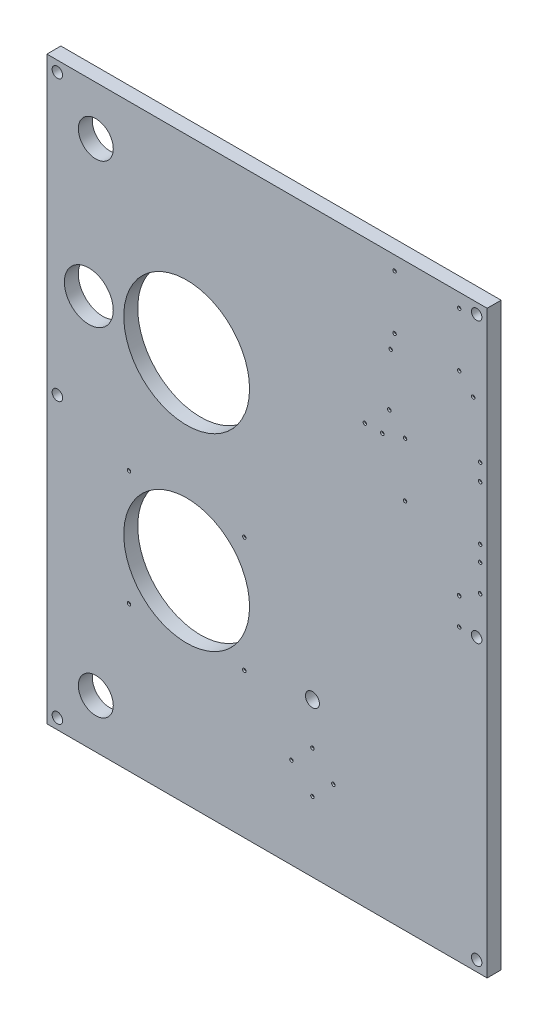
SolidWorks part; units mm, degrees
material "PVC Rigid"
ref_plane "Front Plane" through (0, 0, 0) normal (0, 0, 1) x (1, 0, 0)
ref_plane "Top Plane" through (0, 0, 0) normal (0, 1, 0) x (1, 0, 0)
ref_plane "Right Plane" through (0, 0, 0) normal (1, 0, 0) x (0, 0, -1)
sketch "Sketch2" plane through (0, 0, 0) normal (0, 0, 1) x (1, 0, 0)
  line L0 (-190.5, 254) -> (190.5, 254)
  line L1 (-200.025, -263.525) -> (200.025, -263.525)
  line L2 (-200.025, -263.525) -> (-200.025, 263.525)
  line L3 (-200.025, 263.525) -> (200.025, 263.525)
  line L4 (200.025, -263.525) -> (200.025, 263.525)
  line L5 (-200.025, -263.525) -> (200.025, 263.525) construction
  line L6 (-200.025, 263.525) -> (200.025, -263.525) construction
  line L7 (190.5, -254) -> (190.5, 254)
  line L8 (-190.5, -254) -> (190.5, -254)
  line L9 (-190.5, -254) -> (-190.5, 254)
  circle A0 centre (-190.5, 254) radius 4.7625
  circle A1 centre (190.5, 254) radius 4.7625
  circle A2 centre (-190.5, -254) radius 4.7625
  circle A3 centre (190.5, -254) radius 4.7625
  circle A4 centre (-190.5, 0) radius 4.7625
  circle A5 centre (190.5, 0) radius 4.7625
  point P0 (0, 0)
  dimension "D4" = 9.525
  dimension "D5" = 9.525
  dimension "D6" = 9.525
  dimension "D7" = 9.525
  dimension "D8" = 9.525
  dimension "D9" = 9.525
  dimension "D1" = 508
  dimension "D2" = 381
  dimension "D3" = 9.525
extrude "Boss-Extrude1" add sketch "Sketch2" along normal blind 12.7 contours A5 L7 A1 L0 A0 L9 A4 A2 L8 A3 | L1 L4 L3 L2 A5 L7 A3 L8 A2 L9 A4 A0 L0 A1
sketch "Sketch3" plane through (0, 0, 12.7) normal (0, 0, 1) x (1, 0, 0)
  line L0 (-200.025, 263.525) -> (200.025, 263.525) construction
  line L1 (-200.025, -263.525) -> (-200.025, 263.525) construction
  line L2 (-200.025, -263.525) -> (200.025, -263.525) construction
  line L3 (-182.5625, 198.4375) -> (-20.6375, 198.4375) construction
  line L4 (-20.6375, 198.4375) -> (-20.6375, 36.5125) construction
  line L5 (-20.6375, 36.5125) -> (-182.5625, 36.5125) construction
  line L6 (-182.5625, 36.5125) -> (-182.5625, 198.4375) construction
  circle A0 centre (-155.575, 219.075) radius 15.875
  circle A1 centre (-161.925, 92.075) radius 22.225
  circle A2 centre (-73.025, 92.075) radius 57.15
  circle A3 centre (-73.025, -79.375) radius 57.15
  circle A4 centre (-155.575, -219.075) radius 15.875
  circle A5 centre (-182.5625, 198.4375) radius 1.5875 construction
  circle A6 centre (-20.6375, 198.4375) radius 1.5875 construction
  circle A7 centre (-20.6375, 36.5125) radius 1.5875 construction
  circle A8 centre (-182.5625, 36.5125) radius 1.5875 construction
  dimension "D1" = 31.75
  dimension "D4" = 44.45
  dimension "D9" = 114.3
  dimension "D10" = 114.3
  dimension "D12" = 171.45
  dimension "D13" = 31.75
  dimension "D16" = 3.175
  dimension "D2" = 44.45
  dimension "D3" = 44.45
  dimension "D5" = 38.1
  dimension "D6" = 171.45
  dimension "D7" = 127
  dimension "D8" = 171.45
  dimension "D11" = 127
  dimension "D14" = 44.45
  dimension "D15" = 44.45
  dimension "D17" = 17.4625
  dimension "D18" = 161.925
  dimension "D19" = 161.925
  dimension "D20" = 65.0875
extrude "Cut-Extrude1" cut sketch "Sketch3" against normal through all
sketch "Sketch4" plane through (0, 0, 12.7) normal (0, 0, 1) x (1, 0, 0)
  line L0 (-200.025, -263.525) -> (-200.025, 263.525) construction
  line L1 (200.025, -263.525) -> (200.025, 263.525) construction
  line L2 (-200.025, 263.525) -> (200.025, 263.525) construction
  line L3 (193.675, 263.525) -> (193.675, -263.525) construction
  line L4 (-200.025, -263.525) -> (200.025, -263.525) construction
  line L5 (193.675, 123.825) -> (125.4125, 123.825) construction
  line L6 (125.4125, 123.825) -> (125.4125, 74.6125) construction
  line L7 (125.4125, 74.6125) -> (193.675, 74.6125) construction
  line L8 (125.4125, 117.475) -> (102.3686, 117.475) construction
  line L9 (112.395, 187.325) -> (187.325, 187.325) construction
  line L10 (115.8875, 250.825) -> (174.625, 250.825) construction
  line L11 (115.8875, 250.825) -> (115.8875, 201.6125) construction
  line L12 (115.8875, 201.6125) -> (174.625, 201.6125) construction
  line L13 (174.625, 250.825) -> (174.625, 201.6125) construction
  line L14 (127.526, 139.065) -> (205.4515, 139.065) construction
  line L15 (41.275, -161.925) -> (41.275, -200.025) construction
  circle A0 centre (60.325, -180.975) radius 1.5875
  circle A1 centre (22.225, -180.975) radius 1.5875
  circle A2 centre (41.275, -161.925) radius 1.5875
  circle A3 centre (193.675, 35.7188) radius 1.5875
  circle A4 centre (174.625, 0) radius 1.5875
  circle A5 centre (-73.025, -79.375) radius 57.15 construction
  circle A6 centre (193.675, 60.325) radius 1.5875
  circle A8 centre (193.675, 74.6125) radius 1.5875
  circle A9 centre (193.675, 123.825) radius 1.5875
  circle A10 centre (125.4125, 123.825) radius 1.5875
  circle A11 centre (125.4125, 74.6125) radius 1.5875
  circle A12 centre (88.9, 117.475) radius 1.5875
  circle A13 centre (104.775, 117.475) radius 1.5875
  circle A14 centre (115.8875, 250.825) radius 1.5875
  circle A15 centre (174.625, 250.825) radius 1.5875
  circle A16 centre (174.625, 201.6125) radius 1.5875
  circle A17 centre (115.8875, 201.6125) radius 1.5875
  circle A18 centre (112.395, 187.325) radius 1.5875
  circle A19 centre (187.325, 187.325) radius 1.5875
  circle A20 centre (111.125, 139.065) radius 1.5875
  circle A21 centre (193.675, 139.065) radius 1.5875
  circle A22 centre (41.275, -200.025) radius 1.5875
  circle A23 centre (174.625, 24.6063) radius 1.5875
  line B0 (-125.4125, -26.9875) -> (-20.6375, -26.9875) construction
  line B1 (-125.4125, -26.9875) -> (-125.4125, -131.7625) construction
  line B2 (-125.4125, -131.7625) -> (-20.6375, -131.7625) construction
  line B3 (-20.6375, -26.9875) -> (-20.6375, -131.7625) construction
  circle B4 centre (-125.4125, -26.9875) radius 1.5875
  circle B5 centre (-20.6375, -26.9875) radius 1.5875
  circle B6 centre (-20.6375, -131.7625) radius 1.5875
  circle B7 centre (-125.4125, -131.7625) radius 1.5875
  dimension "D5" = 3.175
  dimension "D6" = 52.3875
  dimension "D4" = 3.175
  dimension "D9" = 3.175
  dimension "D10" = 124.46
  dimension "D15" = 3.175
  dimension "D32" = 3.175
  dimension "D33" = 3.175
  dimension "D8" = 3.175
  dimension "D11" = 3.175
  dimension "D13" = 1.27
  dimension "D7" = 52.3875
  dimension "D12" = 6.35
  dimension "D14" = 203.2
  dimension "D17" = 139.7
  dimension "D18" = 68.2625
  dimension "D19" = 49.2125
  dimension "D20" = 6.35
  dimension "D21" = 15.875
  dimension "D22" = 95.25
  dimension "D23" = 58.7375
  dimension "D24" = 25.4
  dimension "D25" = 12.7
  dimension "D26" = 49.2125
  dimension "D27" = 74.93
  dimension "D28" = 76.2
  dimension "D29" = 12.7
  dimension "D34" = 158.75
  dimension "D35" = 38.1
  dimension "D36" = 63.5
sketch_block_instance "Block1-1"
sketch_block "Block1" parameters "D1"=3.175
extrude "Cut-Extrude2" cut sketch "Sketch4" against normal blind 1.5875
sketch "Sketch7" plane through (0, 0, 12.7) normal (0, 0, 1) x (1, 0, 0)
  line L0 (41.275, -123.825) -> (41.275, -163.5125) construction
  line L1 (200.025, -263.525) -> (200.025, 263.525) construction
  circle A0 centre (41.275, -123.825) radius 6.35
  circle A1 centre (41.275, -161.925) radius 1.5875 construction
  dimension "D2" = 12.7
  dimension "D1" = 39.6875
extrude "Cut-Extrude4" cut sketch "Sketch7" against normal through all
sketch "Sketch8" [suppressed] plane through (0, 0, 12.7) normal (0, 0, 1) x (1, 0, 0)
  line L0 (122.2375, 250.825) -> (168.275, 250.825) construction
  line L1 (122.2375, 253.365) -> (168.275, 253.365)
  line L2 (122.2375, 248.285) -> (168.275, 248.285)
  line L3 (168.275, 250.825) -> (174.625, 250.825) construction
  line L4 (122.2375, 201.6125) -> (168.275, 201.6125) construction
  line L5 (122.2375, 204.1525) -> (168.275, 204.1525)
  line L6 (122.2375, 199.0725) -> (168.275, 199.0725)
  line L7 (115.8875, 201.6125) -> (122.2375, 201.6125) construction
  line L8 (174.625, 244.475) -> (174.625, 207.9625) construction
  line L9 (177.165, 244.475) -> (177.165, 207.9625)
  line L10 (172.085, 244.475) -> (172.085, 207.9625)
  line L11 (145.2562, 250.825) -> (145.2562, 201.6125) construction
  line L12 (115.8875, 244.475) -> (115.8875, 207.9625) construction
  line L13 (113.3475, 244.475) -> (113.3475, 207.9625)
  line L14 (118.4275, 244.475) -> (118.4275, 207.9625)
  line L15 (118.745, 187.325) -> (180.975, 187.325) construction
  line L16 (118.745, 189.865) -> (180.975, 189.865)
  line L17 (118.745, 184.785) -> (180.975, 184.785)
  line L18 (118.745, 187.325) -> (112.395, 187.325) construction
  line L19 (112.395, 187.325) -> (112.395, 139.2316) construction
  line L20 (112.395, 139.2316) -> (193.3575, 139.2316) construction
  line L21 (149.86, 187.325) -> (149.86, 139.2316) construction
  line L22 (112.395, 163.2783) -> (183.6375, 163.2783) construction
  line L23 (118.745, 139.2316) -> (187.0075, 139.2316) construction
  line L24 (118.745, 141.7716) -> (187.0075, 141.7716)
  line L25 (118.745, 136.6916) -> (187.0075, 136.6916)
  line L26 (112.395, 180.975) -> (112.395, 145.5816) construction
  line L27 (109.855, 180.975) -> (109.855, 145.5816)
  line L28 (114.935, 180.975) -> (114.935, 145.5816)
  line L29 (131.7625, 123.825) -> (187.325, 123.825) construction
  line L30 (131.7625, 126.365) -> (187.325, 126.365)
  line L31 (131.7625, 121.285) -> (187.325, 121.285)
  line L32 (127, 123.825) -> (131.7625, 123.825) construction
  line L33 (131.7625, 74.6125) -> (187.325, 74.6125) construction
  line L34 (131.7625, 77.1525) -> (187.325, 77.1525)
  line L35 (131.7625, 72.0725) -> (187.325, 72.0725)
  line L36 (125.4125, 74.6125) -> (131.7625, 74.6125) construction
  line L37 (125.4125, 117.475) -> (125.4125, 80.9625) construction
  line L38 (122.8725, 117.475) -> (122.8725, 80.9625)
  line L39 (127.9525, 117.475) -> (127.9525, 80.9625)
  line L40 (125.4125, 123.825) -> (125.4125, 117.475) construction
  line L41 (159.5437, 123.825) -> (159.5437, 74.6125) construction
  line L42 (193.675, 117.475) -> (193.675, 80.9625) construction
  line L43 (196.215, 117.475) -> (196.215, 80.9625)
  line L44 (191.135, 117.475) -> (191.135, 80.9625)
  line L45 (41.275, -136.525) -> (41.275, -225.425) construction
  line L46 (-3.175, -225.425) -> (85.725, -225.425) construction
  line L47 (-3.175, -225.425) -> (-3.175, -136.525) construction
  line L48 (-3.175, -136.525) -> (85.725, -136.525) construction
  line L49 (85.725, -225.425) -> (85.725, -136.525) construction
  line L50 (22.225, -180.975) -> (60.325, -180.975) construction
  line L51 (3.175, -136.525) -> (79.375, -136.525) construction
  line L52 (3.175, -133.985) -> (79.375, -133.985)
  line L53 (3.175, -139.065) -> (79.375, -139.065)
  line L54 (3.175, -225.425) -> (79.375, -225.425) construction
  line L55 (3.175, -222.885) -> (79.375, -222.885)
  line L56 (3.175, -227.965) -> (79.375, -227.965)
  line L57 (-3.175, -142.875) -> (-3.175, -219.075) construction
  line L58 (-0.635, -142.875) -> (-0.635, -219.075)
  line L59 (-5.715, -142.875) -> (-5.715, -219.075)
  line L60 (85.725, -142.875) -> (85.725, -219.075) construction
  line L61 (83.185, -142.875) -> (83.185, -219.075)
  line L62 (88.265, -142.875) -> (88.265, -219.075)
  line L63 (-180.975, 198.4375) -> (-22.225, 198.4375) construction
  line L64 (-176.2125, 198.4375) -> (-26.9875, 198.4375) construction
  line L65 (-176.2125, 200.9775) -> (-26.9875, 200.9775)
  line L66 (-176.2125, 195.8975) -> (-26.9875, 195.8975)
  line L67 (-182.5625, 196.85) -> (-182.5625, 38.1) construction
  line L68 (-182.5625, 38.1) -> (-182.5625, 36.5125) construction
  line L69 (-182.5625, 36.5125) -> (-108.6079, 36.5125) construction
  line L70 (-20.6375, 36.5125) -> (-20.6375, 198.4375) construction
  line L71 (-20.6375, 117.475) -> (-182.5625, 117.475) construction
  line L72 (-177.0984, 36.5125) -> (-108.6079, 36.5125) construction
  line L73 (-177.1683, 33.9735) -> (-107.95, 33.9735)
  line L74 (-177.0285, 39.0515) -> (-107.95, 39.0515)
  line L75 (-182.5625, 192.0875) -> (-182.5625, 112.7125) construction
  line L76 (-180.0225, 192.0875) -> (-180.0225, 112.7125)
  line L77 (-185.1025, 192.0875) -> (-185.1025, 112.7125)
  line L78 (-101.6, 36.5125) -> (-101.6, 195.8975) construction
  line L79 (-20.6375, 192.0875) -> (-20.6375, 125.4125) construction
  line L80 (-18.0975, 192.0875) -> (-18.0975, 125.4125)
  line L81 (-23.1775, 192.0875) -> (-23.1775, 125.4125)
  line L82 (-26.9875, 36.5125) -> (-20.6375, 36.5125) construction
  arc A0 (122.2375, 253.365) -> (122.2375, 248.285) centre (122.2375, 250.825) ccw
  arc A1 (168.275, 248.285) -> (168.275, 253.365) centre (168.275, 250.825) ccw
  circle A2 centre (115.8875, 250.825) radius 1.5875 construction
  circle A3 centre (174.625, 250.825) radius 1.5875 construction
  arc A4 (118.745, 189.865) -> (118.745, 184.785) centre (118.745, 187.325) ccw
  arc A5 (122.2375, 204.1525) -> (122.2375, 199.0725) centre (122.2375, 201.6125) ccw
  arc A6 (168.275, 199.0725) -> (168.275, 204.1525) centre (168.275, 201.6125) ccw
  circle A7 centre (174.625, 201.6125) radius 1.5875 construction
  arc A8 (177.165, 244.475) -> (172.085, 244.475) centre (174.625, 244.475) ccw
  arc A9 (172.085, 207.9625) -> (177.165, 207.9625) centre (174.625, 207.9625) ccw
  arc A10 (113.3475, 244.475) -> (118.4275, 244.475) centre (115.8875, 244.475) cw
  arc A11 (118.4275, 207.9625) -> (113.3475, 207.9625) centre (115.8875, 207.9625) cw
  arc A12 (180.975, 184.785) -> (180.975, 189.865) centre (180.975, 187.325) ccw
  circle A13 centre (187.325, 187.325) radius 1.5875 construction
  arc A14 (118.745, 141.7716) -> (118.745, 136.6916) centre (118.745, 139.2316) ccw
  arc A15 (187.0075, 136.6916) -> (187.0075, 141.7716) centre (187.0075, 139.2316) ccw
  arc A16 (109.855, 180.975) -> (114.935, 180.975) centre (112.395, 180.975) cw
  arc A17 (114.935, 145.5816) -> (109.855, 145.5816) centre (112.395, 145.5816) cw
  arc A18 (131.7625, 126.365) -> (131.7625, 121.285) centre (131.7625, 123.825) ccw
  arc A19 (187.325, 121.285) -> (187.325, 126.365) centre (187.325, 123.825) ccw
  circle A20 centre (125.4125, 123.825) radius 1.5875 construction
  circle A21 centre (125.4125, 123.825) radius 1.5875 construction
  circle A22 centre (193.675, 123.825) radius 1.5875 construction
  arc A23 (131.7625, 77.1525) -> (131.7625, 72.0725) centre (131.7625, 74.6125) ccw
  arc A24 (187.325, 72.0725) -> (187.325, 77.1525) centre (187.325, 74.6125) ccw
  circle A25 centre (193.675, 74.6125) radius 1.5875 construction
  arc A26 (122.8725, 117.475) -> (127.9525, 117.475) centre (125.4125, 117.475) cw
  arc A27 (127.9525, 80.9625) -> (122.8725, 80.9625) centre (125.4125, 80.9625) cw
  arc A28 (196.215, 117.475) -> (191.135, 117.475) centre (193.675, 117.475) ccw
  arc A29 (191.135, 80.9625) -> (196.215, 80.9625) centre (193.675, 80.9625) ccw
  arc A30 (3.175, -133.985) -> (3.175, -139.065) centre (3.175, -136.525) ccw
  arc A31 (79.375, -139.065) -> (79.375, -133.985) centre (79.375, -136.525) ccw
  arc A32 (3.175, -222.885) -> (3.175, -227.965) centre (3.175, -225.425) ccw
  arc A33 (79.375, -227.965) -> (79.375, -222.885) centre (79.375, -225.425) ccw
  arc A34 (-0.635, -142.875) -> (-5.715, -142.875) centre (-3.175, -142.875) ccw
  arc A35 (-5.715, -219.075) -> (-0.635, -219.075) centre (-3.175, -219.075) ccw
  arc A36 (83.185, -142.875) -> (88.265, -142.875) centre (85.725, -142.875) cw
  arc A37 (88.265, -219.075) -> (83.185, -219.075) centre (85.725, -219.075) cw
  circle A38 centre (-182.5625, 198.4375) radius 1.5875 construction
  circle A39 centre (-20.6375, 198.4375) radius 1.5875 construction
  arc A40 (-176.2125, 200.9775) -> (-176.2125, 195.8975) centre (-176.2125, 198.4375) ccw
  arc A41 (-26.9875, 195.8975) -> (-26.9875, 200.9775) centre (-26.9875, 198.4375) ccw
  circle A42 centre (-182.5625, 36.5125) radius 1.5875 construction
  arc A43 (-177.1683, 33.9735) -> (-177.0285, 39.0515) centre (-177.0984, 36.5125) cw
  circle A44 centre (-182.5625, 198.4375) radius 1.5875
  arc A45 (-180.0225, 192.0875) -> (-185.1025, 192.0875) centre (-182.5625, 192.0875) ccw
  arc A46 (-185.1025, 112.7125) -> (-180.0225, 112.7125) centre (-182.5625, 112.7125) ccw
  arc A47 (-18.0975, 192.0875) -> (-23.1775, 192.0875) centre (-20.6375, 192.0875) ccw
  arc A48 (-23.1775, 125.4125) -> (-18.0975, 125.4125) centre (-20.6375, 125.4125) ccw
  arc A49 (-107.95, 33.9735) -> (-107.95, 39.0515) centre (-107.95, 36.5125) ccw
  circle A50 centre (-20.6375, 198.4375) radius 1.5875
  circle A51 centre (-20.6375, 36.5125) radius 1.5875
  circle A52 centre (-182.5625, 36.5125) radius 1.5875
  text T0 "rPi" font "Century Gothic" height in points 100
  text T1 "ard" font "Century Gothic" height in points 100
  text T4 "AC" font "Century Gothic" height in points 100
  text T5 "air XC" font "Century Gothic" height in points 100
  point P2 (145.2562, 250.825)
  point P16 (145.2562, 201.6125)
  point P28 (174.625, 226.2188)
  point P37 (115.8875, 226.2188)
  point P45 (149.86, 187.325)
  point P65 (152.8762, 139.2316)
  point P72 (112.395, 163.2783)
  point P80 (159.5437, 123.825)
  point P95 (159.5437, 74.6125)
  point P107 (125.4125, 99.2188)
  point P119 (193.675, 99.2188)
  point P136 (41.275, -180.975)
  point P137 (41.275, -180.975)
  point P140 (41.275, -136.525)
  point P147 (41.275, -225.425)
  point P154 (-3.175, -180.975)
  point P161 (85.725, -180.975)
  point P177 (-101.6, 198.4375)
  point P196 (-101.6, 36.5125)
  point P203 (-182.5625, 152.4)
  point P212 (-20.6375, 158.75)
  dimension "D1" = 2.54
  dimension "D6" = 2.54
  dimension "D23" = 2.54
  dimension "D26" = 2.54
  dimension "D27" = 2.54
  dimension "D31" = 2.54
  dimension "D34" = 2.54
  dimension "D37" = 2.54
  dimension "D39" = 2.54
  dimension "D40" = 2.54
  dimension "D41" = 2.54
  dimension "D42" = 2.54
  dimension "D43" = 2.54
  dimension "D44" = 2.54
  dimension "D45" = 2.54
  dimension "D46" = 2.54
  dimension "D47" = 2.54
  dimension "D48" = 3.175
  dimension "D2" = 6.35
  dimension "D3" = 6.35
  dimension "D4" = 6.35
  dimension "D5" = 6.35
  dimension "D7" = 6.35
  dimension "D8" = 6.35
  dimension "D9" = 6.35
  dimension "D10" = 6.35
  dimension "D11" = 6.35
  dimension "D12" = 6.35
  dimension "D13" = 6.35
  dimension "D14" = 6.35
  dimension "D15" = 6.35
  dimension "D16" = 6.35
  dimension "D17" = 6.35
  dimension "D18" = 6.35
  dimension "D19" = 6.35
  dimension "D20" = 6.35
  dimension "D21" = 88.9
  dimension "D22" = 88.9
  dimension "D24" = 6.35
  dimension "D25" = 6.35
  dimension "D28" = 6.35
  dimension "D29" = 6.35
  dimension "D30" = 6.35
  dimension "D32" = 6.35
  dimension "D33" = 6.35
  dimension "D35" = 76.2
  dimension "D36" = 6.35
  dimension "3.25" = 88.9
  dimension "D38" = 6.35
  dimension "D49" = 6.35
  dimension "D50" = 6.35
sketch_block_instance "Block4-1"
sketch_block "Block4"
extrude "Cut-Extrude5" [suppressed] cut sketch "Sketch8" against normal blind 1.5875
